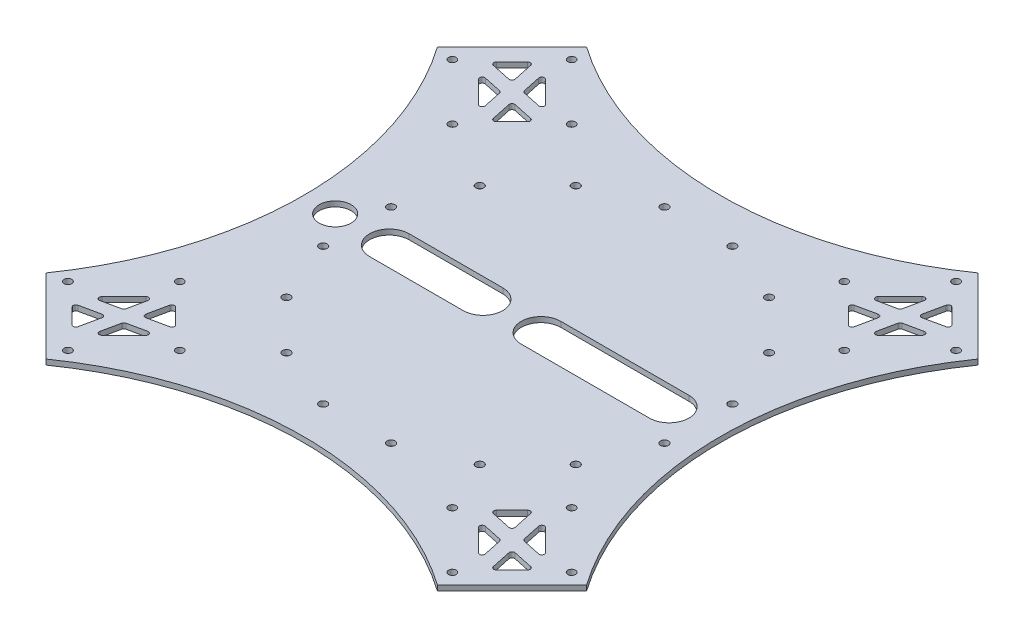
SolidWorks part; units mm, degrees
material "Thornel Mat VMA"
ref_plane "前视基准面" through (0, 0, 0) normal (0, 0, 1) x (1, 0, 0)
ref_plane "上视基准面" through (0, 0, 0) normal (0, 1, 0) x (1, 0, 0)
ref_plane "右视基准面" through (0, 0, 0) normal (1, 0, 0) x (0, 0, -1)
sketch "草图1" plane through (0, 0, 0) normal (0, 1, 0) x (1, 0, 0)
  line L0 (-74.2462, 102.5305) -> (-102.5305, 74.2462)
  line L1 (74.2462, 102.5305) -> (-74.2462, 102.5305)
  line L2 (102.5305, 74.2462) -> (102.5305, -74.2462)
  line L3 (74.2462, -102.5305) -> (-74.2462, -102.5305)
  line L4 (-102.5305, 74.2462) -> (-102.5305, -74.2462)
  line L5 (102.5305, 102.5305) -> (-102.5305, -102.5305) construction
  line L6 (102.5305, -102.5305) -> (-102.5305, 102.5305) construction
  line L7 (102.5305, -74.2462) -> (74.2462, -102.5305)
  line L8 (-102.5305, -74.2462) -> (-74.2462, -102.5305)
  line L9 (74.2462, 102.5305) -> (102.5305, 74.2462)
  line L10 (-102.5305, 102.5305) -> (-102.5305, -102.5305) construction
  line L11 (-102.5305, -102.5305) -> (102.5305, -102.5305) construction
  line L12 (102.5305, -102.5305) -> (102.5305, 102.5305) construction
  line L13 (102.5305, 102.5305) -> (-102.5305, 102.5305) construction
  point P0 (0, 0)
  dimension "D1" = 250
  dimension "D2" = 40
extrude "凸台-拉伸1" add sketch "草图1" along normal blind 2
hole_wizard "孔1" positions "草图4" profile "草图5" legacy
sketch "草图4" plane through (0, 2, 0) normal (0, 1, 0) x (1, 0, 0)
  point P0 (-95.5397, 72.9159)
  point P3 (-74.3265, 51.7027)
  point P6 (-51.6991, 74.3301)
  point P9 (-72.9123, 95.5433)
  point P16 (72.9159, 95.5397)
  point P17 (51.7027, 74.3265)
  point P18 (74.3301, 51.6991)
  point P19 (95.5433, 72.9123)
  point P20 (95.5397, -72.9159)
  point P21 (74.3265, -51.7027)
  point P22 (51.6991, -74.3301)
  point P23 (72.9123, -95.5433)
  point P24 (-72.9159, -95.5397)
  point P25 (-51.7027, -74.3265)
  point P26 (-74.3301, -51.6991)
  point P27 (-95.5433, -72.9123)
  dimension "D1" = 4
sketch "草图5" plane through (-95.5397, 2, -72.9159) normal (1, 0, 0) x (0, 0, 1)
  line L0 (0, 0) -> (0, 100)
  line L1 (0, 100) -> (1.45, 100)
  line L2 (1.45, 100) -> (1.45, 0)
  line L3 (1.45, 0) -> (0, 0)
  line L4 (0, 110) -> (0, -10) construction
  dimension "直径" = 2.9
  dimension "深度" = 100
sketch "草图7" plane through (0, 2, 0) normal (0, 1, 0) x (1, 0, 0)
  line L0 (-95.5397, 72.9159) -> (-51.6991, 74.3301) construction
  line L1 (-86.393, 80.4842) -> (-80.4806, 86.3966)
  line L2 (-84.1601, 71.4358) -> (-75.8066, 63.0823)
  line L3 (-71.4322, 84.1637) -> (-63.0787, 75.8102)
  line L4 (-66.7582, 60.8494) -> (-60.8458, 66.7618)
  line L5 (-89.8008, 77.0764) -> (-57.438, 70.1696) construction
  line L6 (-77.0728, 89.8044) -> (-70.166, 57.4416) construction
  line L7 (-49.2242, 67.6126) -> (-79.6109, 97.9993) construction
  line L8 (-74.2462, 102.5305) -> (-102.5305, 74.2462) construction
  line L9 (-85.8946, 78.7991) -> (-78.378, 77.1949)
  line L10 (-83.2443, 73.1208) -> (-76.36, 71.6516)
  line L11 (-87.6941, 79.1831) -> (-89.8008, 77.0764) construction
  line L12 (-89.8008, 77.0764) -> (-86.5509, 73.8265) construction
  line L13 (-60.6879, 73.4195) -> (-57.438, 70.1696) construction
  line L14 (-57.438, 70.1696) -> (-59.5447, 68.0629) construction
  line L15 (-67.4604, 74.8648) -> (-68.504, 69.975) construction
  line L16 (-73.6194, 73.623) -> (-67.2554, 79.987) construction
  line L17 (-74.1216, 63.9981) -> (-75.5908, 70.8824)
  line L18 (-68.4433, 61.3478) -> (-70.0475, 68.8644)
  line L19 (-70.8788, 75.5944) -> (-63.9945, 74.1252)
  line L20 (-77.1913, 78.3816) -> (-78.7955, 85.8982)
  line L21 (-68.8608, 70.0511) -> (-61.3442, 68.4469)
  line L22 (-71.648, 76.3636) -> (-73.1172, 83.2479)
  line L23 (80.4842, 86.393) -> (86.3966, 80.4806)
  line L24 (71.4358, 84.1601) -> (63.0823, 75.8066)
  line L25 (84.1637, 71.4322) -> (75.8102, 63.0787)
  line L26 (60.8494, 66.7582) -> (66.7618, 60.8458)
  line L27 (78.7991, 85.8946) -> (77.1949, 78.378)
  line L28 (73.1208, 83.2443) -> (71.6516, 76.36)
  line L29 (63.9981, 74.1216) -> (70.8824, 75.5908)
  line L30 (61.3478, 68.4433) -> (68.8644, 70.0475)
  line L31 (75.5944, 70.8788) -> (74.1252, 63.9945)
  line L32 (78.3816, 77.1913) -> (85.8982, 78.7955)
  line L33 (70.0511, 68.8608) -> (68.4469, 61.3442)
  line L34 (76.3636, 71.648) -> (83.2479, 73.1172)
  line L35 (72.9159, 95.5397) -> (74.3301, 51.6991) construction
  line L36 (77.0764, 89.8008) -> (70.1696, 57.438) construction
  line L37 (89.8044, 77.0728) -> (57.4416, 70.166) construction
  line L38 (79.1831, 87.6941) -> (77.0764, 89.8008) construction
  line L39 (77.0764, 89.8008) -> (73.8265, 86.5509) construction
  line L40 (73.4195, 60.6879) -> (70.1696, 57.438) construction
  line L41 (70.1696, 57.438) -> (68.0629, 59.5447) construction
  line L42 (74.8648, 67.4604) -> (69.975, 68.504) construction
  line L43 (73.623, 73.6194) -> (79.987, 67.2554) construction
  line L44 (86.393, -80.4842) -> (80.4806, -86.3966)
  line L45 (84.1601, -71.4358) -> (75.8066, -63.0823)
  line L46 (71.4322, -84.1637) -> (63.0787, -75.8102)
  line L47 (66.7582, -60.8494) -> (60.8458, -66.7618)
  line L48 (85.8946, -78.7991) -> (78.378, -77.1949)
  line L49 (83.2443, -73.1208) -> (76.36, -71.6516)
  line L50 (74.1216, -63.9981) -> (75.5908, -70.8824)
  line L51 (68.4433, -61.3478) -> (70.0475, -68.8644)
  line L52 (70.8788, -75.5944) -> (63.9945, -74.1252)
  line L53 (77.1913, -78.3816) -> (78.7955, -85.8982)
  line L54 (68.8608, -70.0511) -> (61.3442, -68.4469)
  line L55 (71.648, -76.3636) -> (73.1172, -83.2479)
  line L56 (95.5397, -72.9159) -> (51.6991, -74.3301) construction
  line L57 (89.8008, -77.0764) -> (57.438, -70.1696) construction
  line L58 (77.0728, -89.8044) -> (70.166, -57.4416) construction
  line L59 (87.6941, -79.1831) -> (89.8008, -77.0764) construction
  line L60 (89.8008, -77.0764) -> (86.5509, -73.8265) construction
  line L61 (60.6879, -73.4195) -> (57.438, -70.1696) construction
  line L62 (57.438, -70.1696) -> (59.5447, -68.0629) construction
  line L63 (67.4604, -74.8648) -> (68.504, -69.975) construction
  line L64 (73.6194, -73.623) -> (67.2554, -79.987) construction
  line L65 (-80.4842, -86.393) -> (-86.3966, -80.4806)
  line L66 (-71.4358, -84.1601) -> (-63.0823, -75.8066)
  line L67 (-84.1637, -71.4322) -> (-75.8102, -63.0787)
  line L68 (-60.8494, -66.7582) -> (-66.7618, -60.8458)
  line L69 (-78.7991, -85.8946) -> (-77.1949, -78.378)
  line L70 (-73.1208, -83.2443) -> (-71.6516, -76.36)
  line L71 (-63.9981, -74.1216) -> (-70.8824, -75.5908)
  line L72 (-61.3478, -68.4433) -> (-68.8644, -70.0475)
  line L73 (-75.5944, -70.8788) -> (-74.1252, -63.9945)
  line L74 (-78.3816, -77.1913) -> (-85.8982, -78.7955)
  line L75 (-70.0511, -68.8608) -> (-68.4469, -61.3442)
  line L76 (-76.3636, -71.648) -> (-83.2479, -73.1172)
  line L77 (-72.9159, -95.5397) -> (-74.3301, -51.6991) construction
  line L78 (-77.0764, -89.8008) -> (-70.1696, -57.438) construction
  line L79 (-89.8044, -77.0728) -> (-57.4416, -70.166) construction
  line L80 (-79.1831, -87.6941) -> (-77.0764, -89.8008) construction
  line L81 (-77.0764, -89.8008) -> (-73.8265, -86.5509) construction
  line L82 (-73.4195, -60.6879) -> (-70.1696, -57.438) construction
  line L83 (-70.1696, -57.438) -> (-68.0629, -59.5447) construction
  line L84 (-74.8648, -67.4604) -> (-69.975, -68.504) construction
  line L85 (-73.623, -73.6194) -> (-79.987, -67.2554) construction
  arc A0 (-63.0787, 75.8102) -> (-63.9945, 74.1252) centre (-63.7858, 75.1031) cw
  arc A1 (-70.8788, 75.5944) -> (-71.648, 76.3636) centre (-70.67, 76.5724) cw
  arc A2 (-71.4322, 84.1637) -> (-73.1172, 83.2479) centre (-72.1393, 83.4566) ccw
  arc A3 (-78.7955, 85.8982) -> (-80.4806, 86.3966) centre (-79.7735, 85.6895) ccw
  arc A4 (-85.8946, 78.7991) -> (-86.393, 80.4842) centre (-85.6859, 79.7771) cw
  arc A5 (-78.378, 77.1949) -> (-77.1913, 78.3816) centre (-78.1693, 78.1729) ccw
  arc A6 (-66.7582, 60.8494) -> (-68.4433, 61.3478) centre (-67.4653, 61.5565) cw
  arc A7 (-60.8458, 66.7618) -> (-61.3442, 68.4469) centre (-61.5529, 67.4689) ccw
  arc A8 (-68.8608, 70.0511) -> (-70.0475, 68.8644) centre (-69.0695, 69.0731) ccw
  arc A9 (-75.8066, 63.0823) -> (-74.1216, 63.9981) centre (-75.0995, 63.7894) ccw
  arc A10 (-75.5908, 70.8824) -> (-76.36, 71.6516) centre (-76.5688, 70.6736) ccw
  arc A11 (-83.2443, 73.1208) -> (-84.1601, 71.4358) centre (-83.453, 72.1429) ccw
  arc A12 (75.8102, 63.0787) -> (74.1252, 63.9945) centre (75.1031, 63.7858) cw
  arc A13 (75.5944, 70.8788) -> (76.3636, 71.648) centre (76.5724, 70.67) cw
  arc A14 (84.1637, 71.4322) -> (83.2479, 73.1172) centre (83.4566, 72.1393) ccw
  arc A15 (85.8982, 78.7955) -> (86.3966, 80.4806) centre (85.6895, 79.7735) ccw
  arc A16 (78.7991, 85.8946) -> (80.4842, 86.393) centre (79.7771, 85.6859) cw
  arc A17 (77.1949, 78.378) -> (78.3816, 77.1913) centre (78.1729, 78.1693) ccw
  arc A18 (60.8494, 66.7582) -> (61.3478, 68.4433) centre (61.5565, 67.4653) cw
  arc A19 (66.7618, 60.8458) -> (68.4469, 61.3442) centre (67.4689, 61.5529) ccw
  arc A20 (70.0511, 68.8608) -> (68.8644, 70.0475) centre (69.0731, 69.0695) ccw
  arc A21 (63.0823, 75.8066) -> (63.9981, 74.1216) centre (63.7894, 75.0995) ccw
  arc A22 (70.8824, 75.5908) -> (71.6516, 76.36) centre (70.6736, 76.5688) ccw
  arc A23 (73.1208, 83.2443) -> (71.4358, 84.1601) centre (72.1429, 83.453) ccw
  arc A24 (63.0787, -75.8102) -> (63.9945, -74.1252) centre (63.7858, -75.1031) cw
  arc A25 (70.8788, -75.5944) -> (71.648, -76.3636) centre (70.67, -76.5724) cw
  arc A26 (71.4322, -84.1637) -> (73.1172, -83.2479) centre (72.1393, -83.4566) ccw
  arc A27 (78.7955, -85.8982) -> (80.4806, -86.3966) centre (79.7735, -85.6895) ccw
  arc A28 (85.8946, -78.7991) -> (86.393, -80.4842) centre (85.6859, -79.7771) cw
  arc A29 (78.378, -77.1949) -> (77.1913, -78.3816) centre (78.1693, -78.1729) ccw
  arc A30 (66.7582, -60.8494) -> (68.4433, -61.3478) centre (67.4653, -61.5565) cw
  arc A31 (60.8458, -66.7618) -> (61.3442, -68.4469) centre (61.5529, -67.4689) ccw
  arc A32 (68.8608, -70.0511) -> (70.0475, -68.8644) centre (69.0695, -69.0731) ccw
  arc A33 (75.8066, -63.0823) -> (74.1216, -63.9981) centre (75.0995, -63.7894) ccw
  arc A34 (75.5908, -70.8824) -> (76.36, -71.6516) centre (76.5688, -70.6736) ccw
  arc A35 (83.2443, -73.1208) -> (84.1601, -71.4358) centre (83.453, -72.1429) ccw
  arc A36 (-75.8102, -63.0787) -> (-74.1252, -63.9945) centre (-75.1031, -63.7858) cw
  arc A37 (-75.5944, -70.8788) -> (-76.3636, -71.648) centre (-76.5724, -70.67) cw
  arc A38 (-84.1637, -71.4322) -> (-83.2479, -73.1172) centre (-83.4566, -72.1393) ccw
  arc A39 (-85.8982, -78.7955) -> (-86.3966, -80.4806) centre (-85.6895, -79.7735) ccw
  arc A40 (-78.7991, -85.8946) -> (-80.4842, -86.393) centre (-79.7771, -85.6859) cw
  arc A41 (-77.1949, -78.378) -> (-78.3816, -77.1913) centre (-78.1729, -78.1693) ccw
  arc A42 (-60.8494, -66.7582) -> (-61.3478, -68.4433) centre (-61.5565, -67.4653) cw
  arc A43 (-66.7618, -60.8458) -> (-68.4469, -61.3442) centre (-67.4689, -61.5529) ccw
  arc A44 (-70.0511, -68.8608) -> (-68.8644, -70.0475) centre (-69.0731, -69.0695) ccw
  arc A45 (-63.0823, -75.8066) -> (-63.9981, -74.1216) centre (-63.7894, -75.0995) ccw
  arc A46 (-70.8824, -75.5908) -> (-71.6516, -76.36) centre (-70.6736, -76.5688) ccw
  arc A47 (-73.1208, -83.2443) -> (-71.4358, -84.1601) centre (-72.1429, -83.453) ccw
  point P5 (-73.6194, 73.623)
  point P14 (-72.9123, 95.5433)
  point P21 (-67.9822, 72.4199)
  point P38 (-71.5127, 75.7297)
  point P41 (-73.8229, 86.5545)
  point P44 (-79.1795, 87.6977)
  point P50 (-76.8693, 76.8729)
  point P53 (-68.0593, 59.5483)
  point P59 (-70.3695, 70.3731)
  point P62 (-73.4159, 60.6915)
  point P73 (73.623, 73.6194)
  point P84 (72.4199, 67.9822)
  point P126 (73.6194, -73.623)
  point P137 (67.9822, -72.4199)
  point P179 (-73.623, -73.6194)
  point P190 (-72.4199, -67.9822)
  point P230 (0, 0)
  dimension "D4" = 1
  dimension "D1" = 7
  dimension "D2" = 7
  dimension "D3" = 5
  dimension "D5" = 4
extrude "切除-拉伸2" cut sketch "草图7" against normal through all both and the other way through all
sketch "草图8" plane through (0, 2, 0) normal (0, 1, 0) x (1, 0, 0)
  line L0 (-208.5651, 0) -> (0, 0) construction
  line L1 (-102.5305, -74.2462) -> (-50.5427, 0) construction
  line L3 (0, 0) -> (-88.3883, -88.3883) construction
  line L4 (-102.5305, -74.2462) -> (-74.2462, -102.5305) construction
  line L5 (0, 102.5305) -> (0, -102.5305) construction
  line L6 (74.2462, 102.5305) -> (-74.2462, 102.5305) construction
  line L7 (-74.2462, -102.5305) -> (74.2462, -102.5305) construction
  circle A0 centre (-208.5651, 0) radius 129.4443
  circle A2 centre (0, 208.5651) radius 129.4443
  circle A3 centre (208.5651, 0) radius 129.4443
  circle A4 centre (0, -208.5651) radius 129.4443
  point P28 (0, 0)
  dimension "D1" = 10
  dimension "D2" = 4
extrude "切除-拉伸3" cut sketch "草图8" against normal through all both and the other way through all
sketch "草图9" plane through (0, 2, 0) normal (0, 1, 0) x (1, 0, 0)
  line L0 (0, 0) -> (-79.1207, 0) construction
  arc A0 (-102.5305, -74.2462) -> (-102.5305, 74.2462) centre (-208.5651, 0) ccw construction
  circle A1 centre (-67.0707, 0) radius 6.05
  point P8 (-73.1207, 0)
  dimension "D1" = 12.1
  dimension "D2" = 6
extrude "切除-拉伸4" cut sketch "草图9" against normal through all both and the other way through all
sketch "草图11" plane through (0, 2, 0) normal (0, 1, 0) x (1, 0, 0)
  line L0 (5.9793, 0) -> (0, 0) construction
  line L1 (-61.0207, 0) -> (-54.0207, 0) construction
  circle A0 centre (5.9793, 0) radius 60
  circle A1 centre (-67.0707, 0) radius 6.05 construction
  point P3 (-54.0207, 0)
  point P7 (-61.0207, 0)
  dimension "D1" = 120
  dimension "D2" = 7
sketch "草图12" plane through (0, 2, 0) normal (0, 1, 0) x (1, 0, 0)
  line L0 (-58.7526, 12.876) -> (0, 0) construction
  line L1 (-58.7526, 12.876) -> (-58.7526, -12.876) construction
  circle A0 centre (-58.7526, 12.876) radius 1.5
  circle A1 centre (-48.8977, 36.6676) radius 1.5
  circle A2 centre (-30.6884, 54.877) radius 1.5
  circle A3 centre (-6.8967, 64.7318) radius 1.5
  circle A4 centre (18.8552, 64.7318) radius 1.5
  circle A5 centre (42.6469, 54.877) radius 1.5
  circle A6 centre (60.8563, 36.6676) radius 1.5
  circle A7 centre (70.7111, 12.876) radius 1.5
  circle A8 centre (70.7111, -12.876) radius 1.5
  circle A9 centre (60.8563, -36.6676) radius 1.5
  circle A10 centre (42.6469, -54.877) radius 1.5
  circle A11 centre (18.8552, -64.7318) radius 1.5
  circle A12 centre (-6.8967, -64.7318) radius 1.5
  circle A13 centre (-30.6884, -54.877) radius 1.5
  circle A14 centre (-48.8977, -36.6676) radius 1.5
  circle A15 centre (-58.7526, -12.876) radius 1.5
  circle A16 centre (5.9793, 0) radius 60 construction
  point P36 (5.9793, 0)
  dimension "D1" = 3
  dimension "D3" = 66
  dimension "D2" = 16
extrude "切除-拉伸5" cut sketch "草图12" against normal through all both and the other way through all
sketch "草图13" plane through (0, 2, 0) normal (0, 1, 0) x (1, 0, 0)
  line L0 (-46.5207, 0) -> (59.6207, 0) construction
  line L1 (-46.5207, 7.5) -> (-11, 7.5)
  line L2 (-46.5207, -7.5) -> (-11, -7.5)
  line L3 (-11, -7.5) -> (11, -7.5) construction
  line L4 (-61.0207, 0) -> (-46.5207, 0) construction
  line L5 (-46.5207, 0) -> (-11, 0) construction
  line L6 (-46.5207, 7.5) -> (-11, 7.5)
  line L7 (-46.5207, -7.5) -> (-11, -7.5)
  line L8 (11, 0) -> (59.6207, 0) construction
  line L9 (11, 7.5) -> (59.6207, 7.5)
  line L10 (11, -7.5) -> (59.6207, -7.5)
  line L11 (11, 7.5) -> (57.1207, 7.5)
  line L12 (11, -7.5) -> (57.1207, -7.5)
  line L13 (-11, 7.5) -> (11, 7.5) construction
  line L14 (0, 7.5) -> (0, -7.5) construction
  line L15 (67.1207, 0) -> (79.1207, 0) construction
  arc A0 (-46.5207, 7.5) -> (-46.5207, -7.5) centre (-46.5207, 0) ccw
  circle A3 centre (-67.0707, 0) radius 6.05 construction
  arc A4 (-46.5207, 7.5) -> (-46.5207, -7.5) centre (-46.5207, 0) ccw
  arc A5 (-11, -7.5) -> (-11, 7.5) centre (-11, 0) ccw
  arc A6 (11, 7.5) -> (11, -7.5) centre (11, 0) ccw
  arc A7 (59.6207, -7.5) -> (59.6207, 7.5) centre (59.6207, 0) ccw
  point P8 (67.1207, 0)
  point P9 (79.1207, 0)
  point P10 (-61.0207, 0)
  point P14 (-54.0207, 0)
  point P20 (-28.7604, 0)
  point P27 (35.3104, 0)
  point P36 (3.5, 0)
  point P37 (-3.5, 0)
  point P39 (0, 0)
  point P41 (0, 0)
  point P43 (0, 0)
  point P44 (0, 0)
  point P45 (0, 0)
  point P46 (0, 0)
  point P47 (0, 0)
  point P48 (0, 0)
  point P50 (79.1207, 0)
  dimension "D3" = 7.5
  dimension "D1" = 12
  dimension "D2" = 7
  dimension "D4" = 7
extrude "切除-拉伸6" cut sketch "草图13" against normal through all both and the other way through all contours L2 A5 L1 A0 | L10 A7 L9 A6
